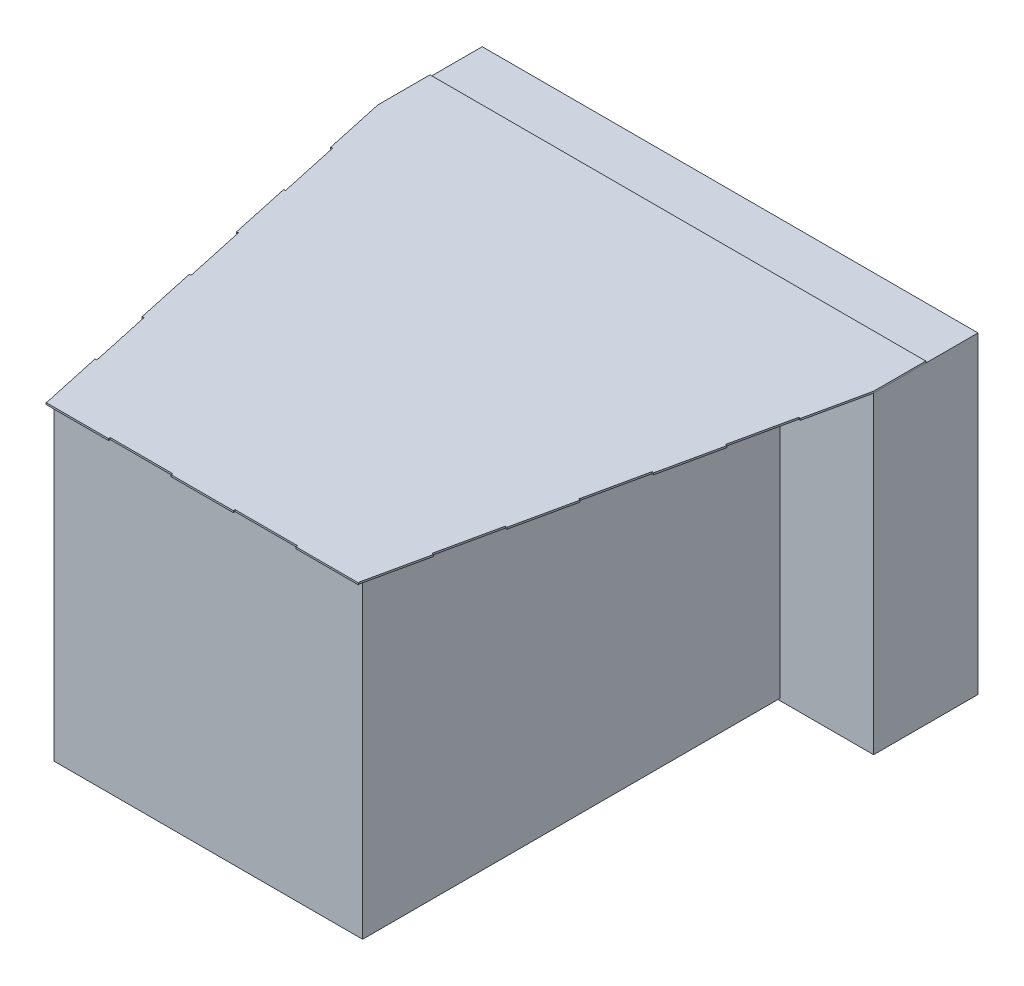
SolidWorks part; units mm, degrees
ref_plane "正面" through (0, 0, 0) normal (0, 0, 1) x (1, 0, 0)
ref_plane "平面" through (0, 0, 0) normal (0, 1, 0) x (1, 0, 0)
ref_plane "右側面" through (0, 0, 0) normal (1, 0, 0) x (0, 0, -1)
sketch "ｽｹｯﾁ1" plane through (0, 0, 0) normal (0, 0, 1) x (1, 0, 0)
  line L1 (-285, 0) -> (285, 0)
  line L2 (-285, 0) -> (-285, 360)
  line L3 (-285, 360) -> (285, 360)
  line L4 (285, 0) -> (285, 360)
  dimension "D1" = 570
  dimension "D2" = 360
extrude "ﾎﾞｽ - 押し出し1" add sketch "ｽｹｯﾁ1" along normal blind 120
sketch "ｽｹｯﾁ2" plane through (0, 0, 0) normal (0, 0, -1) x (-1, 0, 0)
  line L0 (285, 0) -> (-285, 0) construction
  line L1 (265, 0) -> (-265, 0)
  line L2 (265, 0) -> (265, 345)
  line L3 (265, 345) -> (-265, 345)
  line L4 (-265, 0) -> (-265, 345)
  dimension "D1" = 345
  dimension "D2" = 530
extrude "ｶｯﾄ - 押し出し1" cut sketch "ｽｹｯﾁ2" against normal blind 100
sketch "ｽｹｯﾁ4" plane through (0, 0, 120) normal (0, 0, 1) x (1, 0, 0)
  line L0 (0, 0) -> (0, 360) construction
  line L1 (-177.5, 357.5) -> (177.5, 357.5)
  line L2 (-177.5, 357.5) -> (-177.5, 2.5)
  line L3 (-177.5, 2.5) -> (177.5, 2.5)
  line L4 (177.5, 357.5) -> (177.5, 2.5)
  line L5 (-285, 0) -> (285, 0) construction
  line L6 (285, 360) -> (-285, 360) construction
  line L7 (0, 357.5) -> (0, 2.5) construction
  line L8 (-177.5, 180) -> (177.5, 180) construction
  point P14 (0, 180)
  point P15 (0, 0)
  dimension "D1" = 355
  dimension "D2" = 355
extrude "ﾎﾞｽ - 押し出し2" add sketch "ｽｹｯﾁ4" along normal blind 480 separate body
sketch "ｽｹｯﾁ6" plane through (0, 360, 0) normal (0, 1, 0) x (1, 0, 0)
  line L1 (285, -120) -> (285, 0) construction
  line L4 (-285, -60) -> (285, -60)
  line L5 (-254.8571, -258.5714) -> (-239.7857, -327.8571)
  line L6 (-224.7143, -397.1429) -> (-209.6429, -466.4286)
  line L7 (-194.5714, -535.7143) -> (-179.5, -605)
  line L8 (-267.9743, -188.8606) -> (-269.9286, -189.2857)
  line L9 (-252.9028, -258.1463) -> (-267.9743, -188.8606)
  line L10 (-254.8571, -258.5714) -> (-252.9028, -258.1463)
  line L11 (0, -60) -> (0, -605) construction
  line L12 (285, -60) -> (285, -120)
  line L13 (285, -120) -> (269.9286, -189.2857)
  line L14 (107.7, -605) -> (35.9, -605)
  line L16 (-285, -120) -> (-285, -60)
  line L18 (-200.2, 0) -> (200.2, 0) construction
  line L19 (285, -120) -> (-285, -120) construction
  line L20 (179.5, -605) -> (179.5, -607)
  line L21 (179.5, -607) -> (107.7, -607)
  line L22 (107.7, -607) -> (107.7, -605)
  line L23 (35.9, -605) -> (35.9, -607)
  line L24 (35.9, -607) -> (-35.9, -607)
  line L25 (-35.9, -607) -> (-35.9, -605)
  line L26 (-107.7, -605) -> (-107.7, -607)
  line L27 (-107.7, -607) -> (-179.5, -607)
  line L28 (-179.5, -607) -> (-179.5, -605)
  line L29 (-35.9, -605) -> (-107.7, -605)
  line L30 (-237.8314, -327.432) -> (-239.7857, -327.8571)
  line L31 (177.5, -600) -> (-177.5, -600) construction
  line L32 (-222.76, -396.7177) -> (-237.8314, -327.432)
  line L33 (-224.7143, -397.1429) -> (-222.76, -396.7177)
  line L34 (-207.6886, -466.0035) -> (-209.6429, -466.4286)
  line L35 (177.5, -600) -> (177.5, -120) construction
  line L36 (-177.5, -600) -> (-177.5, -120) construction
  line L37 (194.5714, -535.7143) -> (192.6171, -535.2892)
  line L38 (192.6171, -535.2892) -> (207.6886, -466.0035)
  line L39 (207.6886, -466.0035) -> (209.6429, -466.4286)
  line L40 (224.7143, -397.1429) -> (222.76, -396.7177)
  line L41 (222.76, -396.7177) -> (237.8314, -327.432)
  line L42 (237.8314, -327.432) -> (239.7857, -327.8571)
  line L43 (254.8571, -258.5714) -> (252.9028, -258.1463)
  line L44 (252.9028, -258.1463) -> (267.9743, -188.8606)
  line L45 (267.9743, -188.8606) -> (269.9286, -189.2857)
  line L46 (194.5714, -535.7143) -> (179.5, -605)
  line L47 (224.7143, -397.1429) -> (209.6429, -466.4286)
  line L48 (254.8571, -258.5714) -> (239.7857, -327.8571)
  line L49 (-192.6171, -535.2892) -> (-207.6886, -466.0035)
  line L50 (-194.5714, -535.7143) -> (-192.6171, -535.2892)
  line L51 (-285, -120) -> (-269.9286, -189.2857)
  point P43 (192.9749, -543.054)
  point P46 (241.6078, -310.0713)
  point P47 (256.6327, -240.9997)
  point P48 (250.7255, -268.5809)
  dimension "D1" = 60
  dimension "D2" = 5
  dimension "D3" = 2
  dimension "D4" = 2
  dimension "D5" = 2
  dimension "D6" = 2
extrude "ﾎﾞｽ - 押し出し3" add sketch "ｽｹｯﾁ6" along normal blind 2 separate body
sketch "ｽｹｯﾁ8" plane through (0, 0, 0) normal (0, -1, 0) x (1, 0, 0)
  line L40 (285, 60) -> (285, 120)
  line L41 (-285, 60) -> (285, 60)
  line L42 (-285, 120) -> (-285, 60)
  line L43 (-269.9286, 189.2857) -> (-285, 120)
  line L44 (-267.9743, 188.8606) -> (-269.9286, 189.2857)
  line L45 (-252.9028, 258.1463) -> (-267.9743, 188.8606)
  line L46 (-254.8571, 258.5714) -> (-252.9028, 258.1463)
  line L47 (-239.7857, 327.8571) -> (-254.8571, 258.5714)
  line L48 (-237.8314, 327.432) -> (-239.7857, 327.8571)
  line L49 (-222.76, 396.7177) -> (-237.8314, 327.432)
  line L50 (-224.7143, 397.1429) -> (-222.76, 396.7177)
  line L51 (-209.6429, 466.4286) -> (-224.7143, 397.1429)
  line L52 (-207.6886, 466.0035) -> (-209.6429, 466.4286)
  line L53 (-192.6171, 535.2892) -> (-207.6886, 466.0035)
  line L54 (-194.5714, 535.7143) -> (-192.6171, 535.2892)
  line L55 (-179.5, 605) -> (-194.5714, 535.7143)
  line L56 (-179.5, 607) -> (-179.5, 605)
  line L57 (-107.7, 607) -> (-179.5, 607)
  line L58 (-107.7, 605) -> (-107.7, 607)
  line L59 (-35.9, 605) -> (-107.7, 605)
  line L60 (-35.9, 607) -> (-35.9, 605)
  line L61 (35.9, 607) -> (-35.9, 607)
  line L62 (35.9, 605) -> (35.9, 607)
  line L63 (107.7, 605) -> (35.9, 605)
  line L64 (107.7, 607) -> (107.7, 605)
  line L65 (179.5, 607) -> (107.7, 607)
  line L66 (179.5, 605) -> (179.5, 607)
  line L67 (194.5714, 535.7143) -> (179.5, 605)
  line L68 (192.6171, 535.2892) -> (194.5714, 535.7143)
  line L69 (207.6886, 466.0035) -> (192.6171, 535.2892)
  line L70 (209.6429, 466.4286) -> (207.6886, 466.0035)
  line L71 (224.7143, 397.1429) -> (209.6429, 466.4286)
  line L72 (222.76, 396.7177) -> (224.7143, 397.1429)
  line L73 (237.8314, 327.432) -> (222.76, 396.7177)
  line L74 (239.7857, 327.8571) -> (237.8314, 327.432)
  line L75 (254.8571, 258.5714) -> (239.7857, 327.8571)
  line L76 (252.9028, 258.1463) -> (254.8571, 258.5714)
  line L77 (267.9743, 188.8606) -> (252.9028, 258.1463)
  line L78 (269.9286, 189.2857) -> (267.9743, 188.8606)
  line L79 (285, 120) -> (269.9286, 189.2857)
  line L80 (285, 60) -> (285, 120)
  line L81 (-285, 60) -> (285, 60)
  line L82 (-285, 120) -> (-285, 60)
  line L83 (-269.9286, 189.2857) -> (-285, 120)
  line L84 (-267.9743, 188.8606) -> (-269.9286, 189.2857)
  line L85 (-252.9028, 258.1463) -> (-267.9743, 188.8606)
  line L86 (-254.8571, 258.5714) -> (-252.9028, 258.1463)
  line L87 (-239.7857, 327.8571) -> (-254.8571, 258.5714)
  line L88 (-237.8314, 327.432) -> (-239.7857, 327.8571)
  line L89 (-222.76, 396.7177) -> (-237.8314, 327.432)
  line L90 (-224.7143, 397.1429) -> (-222.76, 396.7177)
  line L91 (-209.6429, 466.4286) -> (-224.7143, 397.1429)
  line L92 (-207.6886, 466.0035) -> (-209.6429, 466.4286)
  line L93 (-192.6171, 535.2892) -> (-207.6886, 466.0035)
  line L94 (-194.5714, 535.7143) -> (-192.6171, 535.2892)
  line L95 (-179.5, 605) -> (-194.5714, 535.7143)
  line L96 (-179.5, 607) -> (-179.5, 605)
  line L97 (-107.7, 607) -> (-179.5, 607)
  line L98 (-107.7, 605) -> (-107.7, 607)
  line L99 (-35.9, 605) -> (-107.7, 605)
  line L100 (-35.9, 607) -> (-35.9, 605)
  line L101 (35.9, 607) -> (-35.9, 607)
  line L102 (35.9, 605) -> (35.9, 607)
  line L103 (107.7, 605) -> (35.9, 605)
  line L104 (107.7, 607) -> (107.7, 605)
  line L105 (179.5, 607) -> (107.7, 607)
  line L106 (179.5, 605) -> (179.5, 607)
  line L107 (194.5714, 535.7143) -> (179.5, 605)
  line L108 (192.6171, 535.2892) -> (194.5714, 535.7143)
  line L109 (207.6886, 466.0035) -> (192.6171, 535.2892)
  line L110 (209.6429, 466.4286) -> (207.6886, 466.0035)
  line L111 (224.7143, 397.1429) -> (209.6429, 466.4286)
  line L112 (222.76, 396.7177) -> (224.7143, 397.1429)
  line L113 (237.8314, 327.432) -> (222.76, 396.7177)
  line L114 (239.7857, 327.8571) -> (237.8314, 327.432)
  line L115 (254.8571, 258.5714) -> (239.7857, 327.8571)
  line L116 (252.9028, 258.1463) -> (254.8571, 258.5714)
  line L117 (267.9743, 188.8606) -> (252.9028, 258.1463)
  line L118 (269.9286, 189.2857) -> (267.9743, 188.8606)
  line L119 (285, 120) -> (269.9286, 189.2857)
  dimension "D1" = 0
